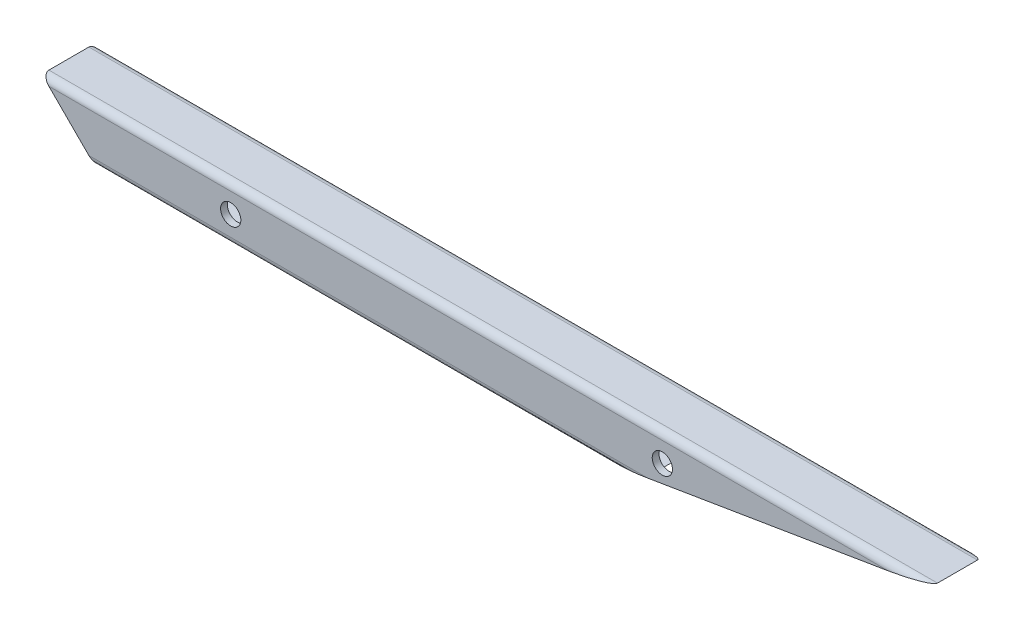
SolidWorks part; units mm, degrees
material "6061 Alloy"
ref_plane "Front Plane" through (0, 0, 0) normal (0, 0, 1) x (1, 0, 0)
ref_plane "Top Plane" through (0, 0, 0) normal (0, 1, 0) x (1, 0, 0)
ref_plane "Right Plane" through (0, 0, 0) normal (1, 0, 0) x (0, 0, -1)
sketch "Sketch1" plane through (0, 0, 0) normal (1, 0, 0) x (0, 0, -1)
  line L1 (3.302, 0) -> (22.098, 0)
  line L2 (0, 3.302) -> (0, 22.098)
  line L3 (3.302, 25.4) -> (22.098, 25.4)
  line L4 (25.4, 3.302) -> (25.4, 22.098)
  line L5 (6.223, 3.175) -> (19.177, 3.175)
  line L6 (3.175, 6.223) -> (3.175, 19.177)
  line L7 (6.223, 22.225) -> (19.177, 22.225)
  line L8 (22.225, 6.223) -> (22.225, 19.177)
  arc A0 (19.177, 22.225) -> (22.225, 19.177) centre (19.177, 19.177) cw
  arc A1 (19.177, 3.175) -> (22.225, 6.223) centre (19.177, 6.223) ccw
  arc A2 (6.223, 3.175) -> (3.175, 6.223) centre (6.223, 6.223) cw
  arc A3 (3.175, 19.177) -> (6.223, 22.225) centre (6.223, 19.177) cw
  arc A4 (22.098, 0) -> (25.4, 3.302) centre (22.098, 3.302) ccw
  arc A5 (3.302, 0) -> (0, 3.302) centre (3.302, 3.302) cw
  arc A6 (0, 22.098) -> (3.302, 25.4) centre (3.302, 22.098) cw
  arc A7 (22.098, 25.4) -> (25.4, 22.098) centre (22.098, 22.098) cw
  point P9 (12.7, 22.225)
  point P10 (12.7, 25.4)
  point P11 (0, 12.7)
  point P12 (3.175, 12.7)
  point P23 (25.4, 0)
  point P26 (0, 0)
  dimension "D3" = 3.048
  dimension "D4" = 3.302
  dimension "D1" = 3.175
  dimension "D2" = 25.4
extrude "Boss-Extrude1" add sketch "Sketch1" along normal blind 418.338
sketch "Sketch2" plane through (0, 0, 0) normal (0, 0, 1) x (1, 0, 0)
  line L0 (0, 22.098) -> (0, 3.302) construction
  line L1 (0, 0) -> (0, 25.4)
  line L2 (0, 25.4) -> (25.4, 0)
  line L3 (418.338, 0) -> (0, 0) construction
  line L4 (25.4, 0) -> (0, 0)
  line L5 (418.338, 0) -> (265.303, 0)
  line L6 (265.303, 0) -> (418.338, 25.4)
  line L7 (418.338, 25.4) -> (418.338, 0)
  circle A0 centre (88.9, 12.7) radius 4.7625
  circle A1 centre (292.1, 12.7) radius 4.7625
  point P9 (0, 12.7)
  dimension "D3" = 9.525
  dimension "D5" = 9.525
  dimension "D1" = 203.2
  dimension "D2" = 88.9
  dimension "D4" = 153.035
extrude "Cut-Extrude1" cut sketch "Sketch2" against normal through all
equation "\"D1@Boss-Extrude1\"=12.5"
